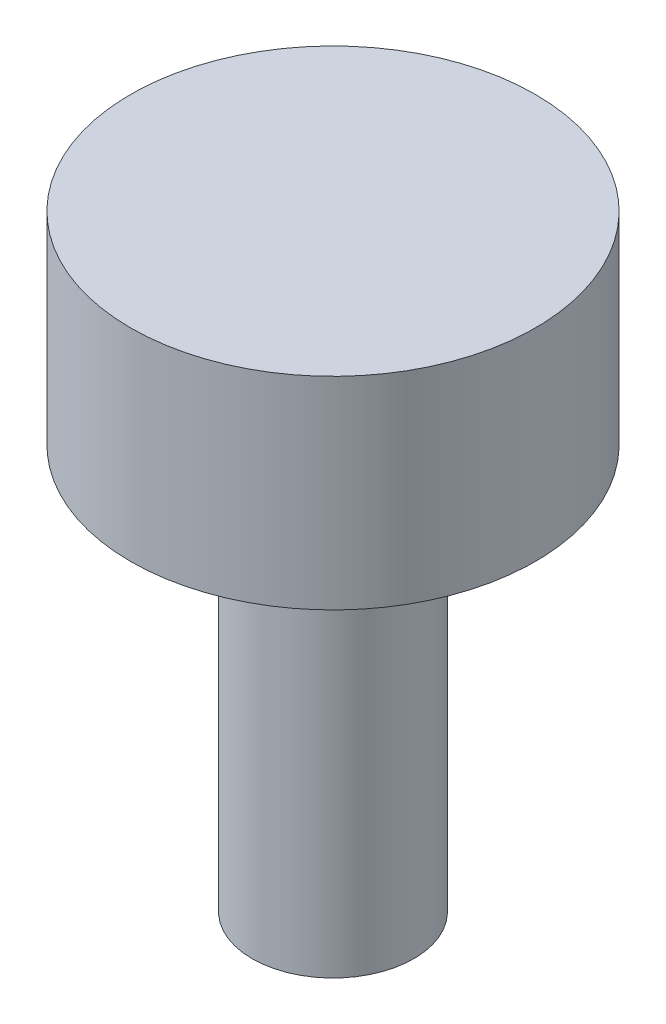
SolidWorks part; units mm, degrees
ref_plane "Front Plane" through (0, 0, 0) normal (0, 0, 1) x (1, 0, 0)
ref_plane "Top Plane" through (0, 0, 0) normal (0, 1, 0) x (1, 0, 0)
ref_plane "Right Plane" through (0, 0, 0) normal (1, 0, 0) x (0, 0, -1)
sketch "Sketch1" plane through (0, 0, 0) normal (0, 1, 0) x (1, 0, 0)
  circle A0 centre (0, 0) radius 1
  dimension "D1" = 2
extrude "Boss-Extrude1" add sketch "Sketch1" along normal blind 5
sketch "Sketch2" plane through (0, 5, 0) normal (0, 1, 0) x (1, 0, 0)
  circle A0 centre (0, 0) radius 2.5
  dimension "D1" = 5
extrude "Boss-Extrude2" add sketch "Sketch2" along normal blind 2.5
